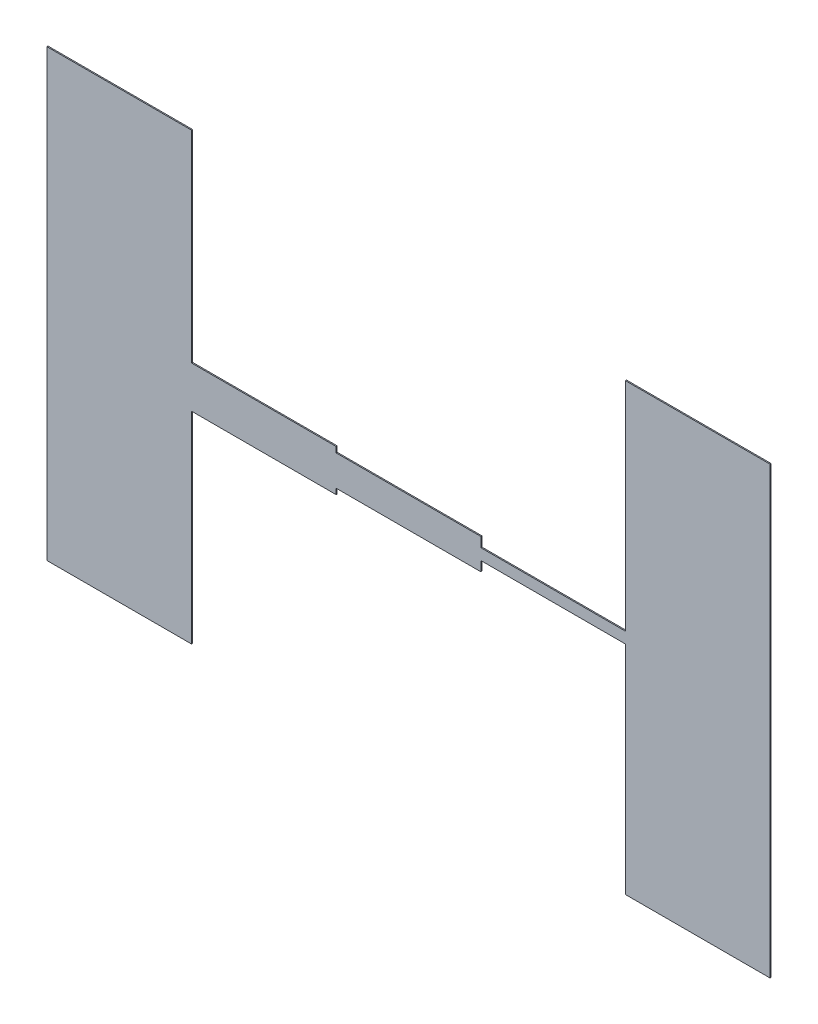
SolidWorks part; units mm, degrees
ref_plane "Front Plane" through (0, 0, 0) normal (0, 0, 1) x (1, 0, 0)
ref_plane "Top Plane" through (0, 0, 0) normal (0, 1, 0) x (1, 0, 0)
ref_plane "Right Plane" through (0, 0, 0) normal (1, 0, 0) x (0, 0, -1)
sketch "Sketch1" plane through (0, 0, 0) normal (0, 0, 1) x (1, 0, 0)
  line L0 (0, 0) -> (650, 0)
  line L1 (-650, -2000) -> (650, -2000)
  line L2 (-650, -2000) -> (-650, 2000)
  line L3 (-650, 2000) -> (650, 2000)
  line L4 (650, -2000) -> (650, -187.5)
  line L5 (-650, -2000) -> (650, 2000) construction
  line L6 (-650, 2000) -> (650, -2000) construction
  line L7 (650, 0) -> (7529.1767, 0) construction
  line L8 (650, 187.5) -> (650, 2000)
  line L9 (1950, -187.5) -> (650, -187.5)
  line L10 (1950, -187.5) -> (1950, -137.5)
  line L11 (1950, 187.5) -> (650, 187.5)
  line L13 (1950, -187.5) -> (650, 187.5) construction
  line L14 (1950, 187.5) -> (650, -187.5) construction
  line L15 (3250, -137.5) -> (1950, -137.5)
  line L16 (3250, -137.5) -> (3250, -50)
  line L17 (3250, 137.5) -> (1950, 137.5)
  line L19 (3250, -137.5) -> (1950, 137.5) construction
  line L20 (3250, 137.5) -> (1950, -137.5) construction
  line L21 (4550, -50) -> (3250, -50)
  line L23 (4550, 50) -> (3250, 50)
  line L25 (4550, -50) -> (3250, 50) construction
  line L26 (4550, 50) -> (3250, -50) construction
  line L27 (1950, 137.5) -> (1950, 187.5)
  line L28 (3250, 50) -> (3250, 137.5)
  line L29 (4550, 50) -> (4550, 2000)
  line L30 (5850, -2000) -> (4550, -2000)
  line L31 (5850, -2000) -> (5850, 2000)
  line L32 (5850, 2000) -> (4550, 2000)
  line L33 (4550, -2000) -> (4550, -50)
  line L34 (5850, -2000) -> (4550, 2000) construction
  line L35 (5850, 2000) -> (4550, -2000) construction
  point P0 (0, 0)
  point P9 (1300, 0)
  point P14 (2600, 0)
  point P19 (3900, 0)
  point P24 (5200, 0)
  dimension "D1" = 1300
  dimension "D2" = 4000
  dimension "D3" = 375
  dimension "D4" = 1300
  dimension "D5" = 1300
  dimension "D6" = 1300
  dimension "D7" = 100
  dimension "D8" = 275
  dimension "D9" = 1300
  dimension "D10" = 4000
extrude "Boss-Extrude1" add sketch "Sketch1" along normal blind 10
